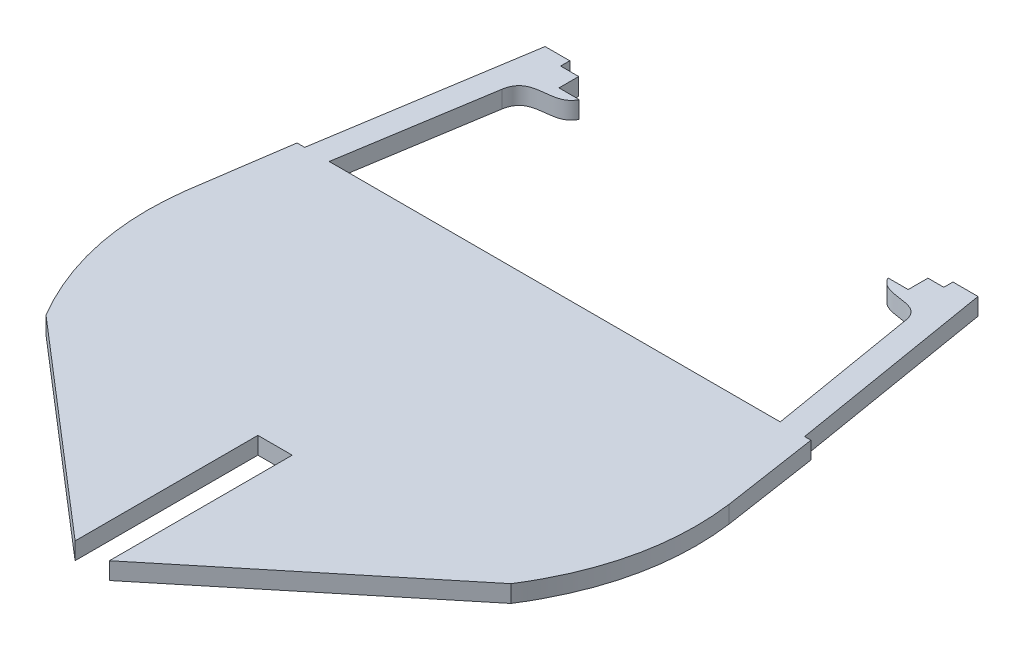
SolidWorks part; units mm, degrees
ref_plane "前视基准面" through (0, 0, 0) normal (0, 0, 1) x (1, 0, 0)
ref_plane "上视基准面" through (0, 0, 0) normal (0, 1, 0) x (1, 0, 0)
ref_plane "右视基准面" through (0, 0, 0) normal (1, 0, 0) x (0, 0, -1)
sketch "草图1" plane through (0, 0, 0) normal (0, 1, 0) x (1, 0, 0)
  line L0 (105.1232, 0) -> (0, 0)
  line L1 (0, 0) -> (5.5478, 34.7092)
  line L2 (105.1232, 0) -> (99.291, 34.7092)
  line L3 (115.792, -22.6179) -> (112.3964, -0.1214)
  line L4 (105.1232, 0) -> (0, 0)
  line L5 (112.3964, -0.1214) -> (110.9194, -0.1214)
  line L6 (110.9194, -0.1214) -> (102.8472, 48.3652)
  line L7 (102.8472, 48.3652) -> (97.015, 48.3652)
  line L8 (97.015, 48.3652) -> (97.015, 46.2315)
  line L9 (97.015, 46.2315) -> (93.3164, 46.2315)
  line L10 (93.3164, 46.2315) -> (93.3164, 41.6256)
  line L11 (93.3164, 41.6256) -> (88.6222, 41.6256)
  line L12 (-5.7053, 0) -> (-7.4936, 0)
  line L13 (-7.4936, 0) -> (-10.8149, -22.6179)
  line L14 (-5.7053, 0) -> (1.9591, 48.3652)
  line L15 (1.9591, 48.3652) -> (7.7073, 48.3652)
  line L16 (7.7073, 48.3652) -> (7.7073, 46.2315)
  line L17 (7.7073, 46.2315) -> (11.9227, 46.2315)
  line L18 (11.9227, 46.2315) -> (11.9227, 41.6256)
  line L19 (11.9227, 41.6256) -> (16.6491, 41.6256)
  line L20 (106.4106, -64.0108) -> (54.9681, -106.1866)
  line L21 (54.9681, -106.1866) -> (54.9681, -63.5866)
  line L22 (54.9681, -63.5866) -> (46.9681, -63.5866)
  line L23 (46.9681, -63.5866) -> (46.9681, -106.1866)
  line L24 (46.9681, -106.1866) -> (-1.989, -64.0108)
  spline S0 degree 3 poles (88.6222, 41.6256) (91.0293, 36.9043) (98.5719, 41.1781) (99.291, 34.7092) knots 0 0 0 0 1 1 1 1
  spline S1 degree 3 poles (16.6491, 41.6256) (14.2964, 36.8893) (6.7076, 41.3985) (5.5478, 34.7092) knots 0 0 0 0 1 1 1 1
  spline S2 degree 2 poles (115.792, -22.6179) (118.6725, -44.5337) (106.4106, -64.0108) knots 0 0 0 1 1 1
  spline S3 degree 2 poles (-10.8149, -22.6179) (-13.5831, -44.4263) (-1.989, -64.0108) knots 0 0 0 1 1 1
  dimension "D2" = 42.6
sketch "草图2" plane through (0, 0, 0) normal (0, 0, 1) x (1, 0, 0)
  line L0 (54.9681, 0) -> (46.9681, 0) construction
extrude "凸台-拉伸2" add sketch "草图1" along normal blind 4 contours L13 S3 L24 L23 L22 L21 L20 S2 L3 L5 L6 L7 L8 L9 L10 L11 S0 L2 L0 L1 S1 L19 L18 L17 L16 L15 L14 L12
